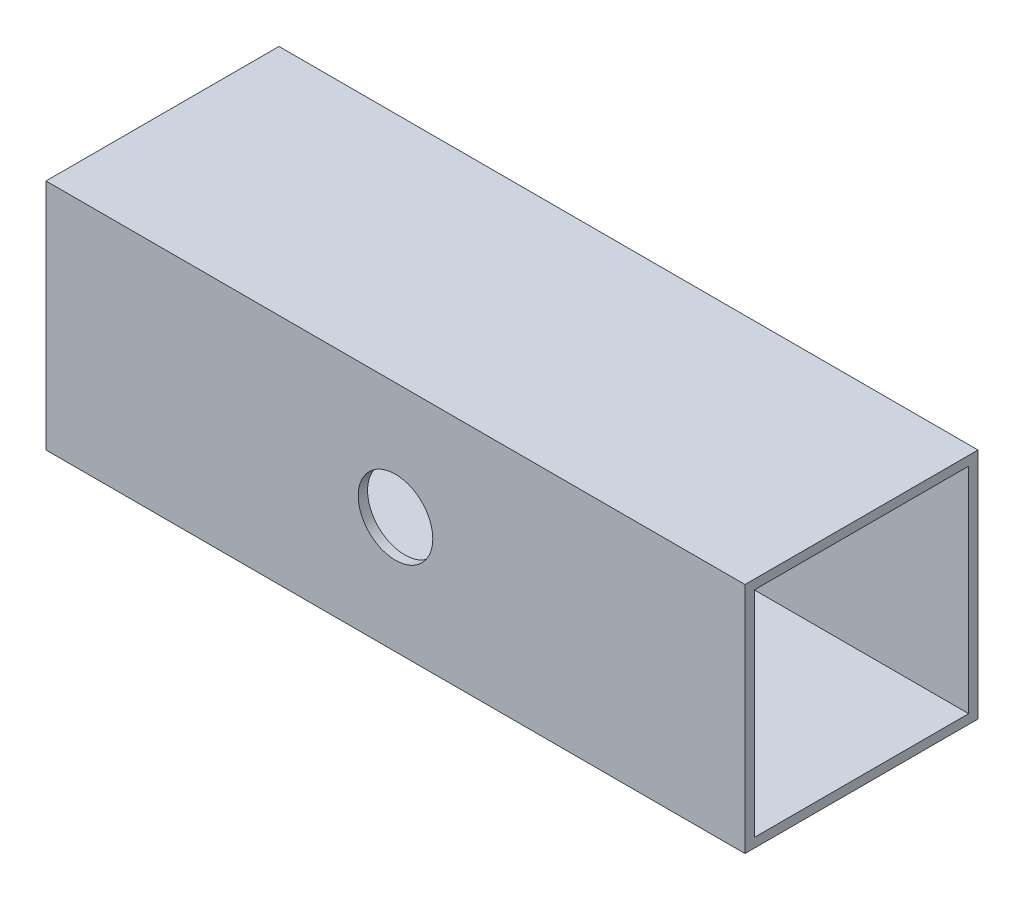
SolidWorks part; units mm, degrees
ref_plane "Front Plane" through (0, 0, 0) normal (0, 0, 1) x (1, 0, 0)
ref_plane "Top Plane" through (0, 0, 0) normal (0, 1, 0) x (1, 0, 0)
ref_plane "Right Plane" through (0, 0, 0) normal (1, 0, 0) x (0, 0, -1)
sketch "Sketch1" plane through (0, 0, 0) normal (1, 0, 0) x (0, 0, -1)
  line L0 (-11.5, 11.5) -> (11.5, 11.5)
  line L1 (-12.5, -12.5) -> (12.5, -12.5)
  line L2 (-12.5, -12.5) -> (-12.5, 12.5)
  line L3 (-12.5, 12.5) -> (12.5, 12.5)
  line L4 (12.5, -12.5) -> (12.5, 12.5)
  line L5 (-12.5, -12.5) -> (12.5, 12.5) construction
  line L6 (-12.5, 12.5) -> (12.5, -12.5) construction
  line L7 (11.5, -11.5) -> (11.5, 11.5)
  line L8 (-11.5, -11.5) -> (11.5, -11.5)
  line L9 (-11.5, -11.5) -> (-11.5, 11.5)
  point P0 (0, 0)
  dimension "D2" = 25
  dimension "D1" = 1
extrude "Boss-Extrude1" add sketch "Sketch1" along normal blind 75
sketch "Sketch2" plane through (0, 0, 12.5) normal (0, 0, 1) x (1, 0, 0)
  line L0 (0, 0) -> (75, 0) construction
  line L1 (75, 12.5) -> (75, -12.5) construction
  circle A0 centre (37.5, 0) radius 4
  dimension "D1" = 8
extrude "Cut-Extrude1" cut sketch "Sketch2" against normal through all
